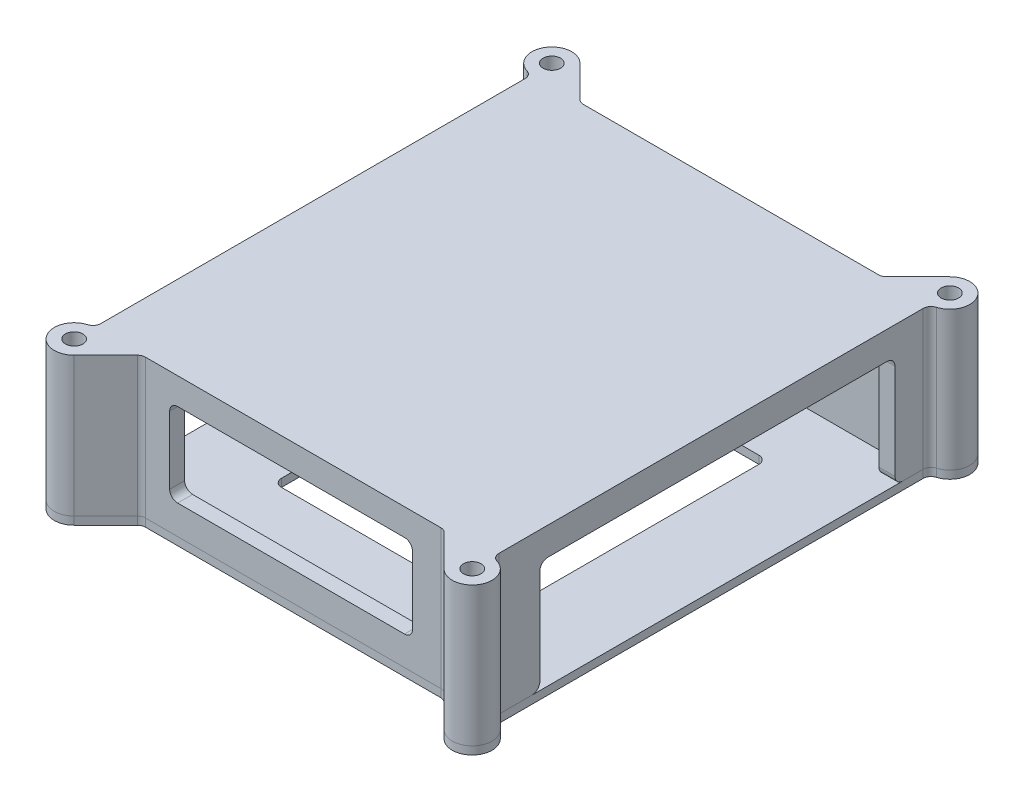
SolidWorks part; units mm, degrees
ref_plane "Front Plane" through (0, 0, 0) normal (0, 0, 1) x (1, 0, 0)
ref_plane "Top Plane" through (0, 0, 0) normal (0, 1, 0) x (1, 0, 0)
ref_plane "Right Plane" through (0, 0, 0) normal (1, 0, 0) x (0, 0, -1)
sketch "Sketch1" plane through (0, 0, 0) normal (0, 1, 0) x (1, 0, 0)
  line L1 (0, 0) -> (127, 0)
  line L2 (0, 0) -> (0, 139.7)
  line L3 (0, 139.7) -> (127, 139.7)
  line L4 (127, 0) -> (127, 139.7)
  dimension "D1" = 127
  dimension "D2" = 139.7
extrude "Boss-Extrude1" add sketch "Sketch1" along normal blind 44.45
sketch "Sketch3" plane through (0, 0, 0) normal (0, -1, 0) x (1, 0, 0)
  line L0 (0, -139.7) -> (0, 0) construction
  line L1 (6.35, -4.7625) -> (121.92, -4.7625)
  line L2 (6.35, -4.7625) -> (6.35, -135.8265)
  line L3 (6.35, -135.8265) -> (121.92, -135.8265)
  line L4 (121.92, -4.7625) -> (121.92, -135.8265)
  line L5 (0, 0) -> (127, 0) construction
  dimension "D1" = 115.57
  dimension "D2" = 131.064
  dimension "D3" = 6.35
  dimension "D4" = 4.7625
extrude "Cut-Extrude1" cut sketch "Sketch3" against normal blind 44
sketch "Sketch4" plane through (0, 0, -139.7) normal (0, 0, -1) x (-1, 0, 0)
  line L0 (-127, 0) -> (0, 0) construction
  line L1 (-101.6, 35.941) -> (-24.13, 35.941)
  line L2 (-101.6, 35.941) -> (-101.6, 9.271)
  line L3 (-101.6, 9.271) -> (-24.13, 9.271)
  line L4 (-24.13, 35.941) -> (-24.13, 9.271)
  line L7 (-127, 44.45) -> (-127, 0) construction
  dimension "D1" = 26.67
  dimension "D2" = 77.47
  dimension "D3" = 9.271
  dimension "D4" = 25.4
extrude "Cut-Extrude2" cut sketch "Sketch4" against normal blind 190.754
sketch "Sketch5" plane through (127, 0, 0) normal (1, 0, 0) x (0, 0, -1)
  line L0 (0, 44.45) -> (139.7, 44.45) construction
  line L1 (15.24, 35.56) -> (128.524, 35.56)
  line L2 (15.24, 35.56) -> (15.24, -11.43)
  line L3 (15.24, -11.43) -> (128.524, -11.43)
  line L4 (128.524, 35.56) -> (128.524, -11.43)
  line L6 (0, 44.45) -> (0, 0) construction
  dimension "D1" = 46.99
  dimension "D2" = 113.284
  dimension "D3" = 8.89
  dimension "D4" = 15.24
extrude "Cut-Extrude3" cut sketch "Sketch5" against normal blind 190.754 contours L2 L1 L4 L3
sketch "Sketch6" plane through (0, 0, 0) normal (0, -1, 0) x (-1, 0, 0)
  line L6 (0, 0) -> (-127, 0) construction
  line L7 (-127, 146.05) -> (0, 146.05) construction
  line L8 (-127, 146.05) -> (-127, -6.35) construction
  line L9 (-127, -6.35) -> (0, -6.35) construction
  line L10 (0, 146.05) -> (0, -6.35) construction
  line L12 (-122.5099, 150.5401) -> (-111.6697, 139.7)
  line L13 (-127, 139.7) -> (0, 139.7) construction
  line L14 (-4.4901, 150.5401) -> (-15.3303, 139.7)
  line L15 (-4.4901, -10.8401) -> (-15.3303, 0)
  line L16 (-122.5099, -10.8401) -> (-111.6697, 0)
  line L17 (-127, 0) -> (-111.6697, 0)
  line L18 (-15.3303, 0) -> (0, 0)
  line L19 (-127, 0) -> (-127, 15.24) construction
  line L20 (-127, 139.7) -> (0, 139.7)
  circle A0 centre (0, -6.35) radius 2.794
  circle A1 centre (-127, -6.35) radius 2.794
  circle A2 centre (0, 146.05) radius 2.794
  circle A3 centre (-127, 146.05) radius 2.794
  circle A4 centre (-127, -6.35) radius 6.35
  circle A5 centre (0, -6.35) radius 6.35
  circle A6 centre (0, 146.05) radius 6.35
  circle A7 centre (-127, 146.05) radius 6.35
  line M3 (-127, 0) -> (0, 0)
  dimension "D1" = 5.588
  dimension "D2" = 5.588
  dimension "D3" = 5.588
  dimension "D4" = 5.588
  dimension "D6" = 152.4
  dimension "D5" = 127
ref_plane "Plane1" through (63.5, 0, 0) normal (1, 0, 0) x (0, 0, -1)
ref_plane "Plane4" through (0, 0, -69.85) normal (0, 0, -1) x (-1, 0, 0)
extrude "Boss-Extrude2" add sketch "Sketch6" against normal through all contours A7 A3 | A7 L20 L12 | A6 L14 L20 | A4 A1 | A4 L16 M3 | A5 L15 M3 | A5 A0 | A6 A2
fillet "Fillet1" radius 2.54 24 edges at (0, 22.225, -139.7) (15.3303, 22.225, -139.7) (127, 22.225, -139.7) (127, 22.225, 0) (111.6697, 22.225, 0) (15.3303, 22.225, 0) (0, 22.225, 0) (111.6697, 22.225, -139.7) (24.13, 9.271, -2.3813) (101.6, 9.271, -2.3813) (101.6, 35.941, -2.3813) (24.13, 35.941, -2.3813) (24.13, 9.271, -137.7632) (101.6, 9.271, -137.7632) (101.6, 35.941, -137.7632) (24.13, 35.941, -137.7632) (3.175, 0, -128.524) (3.175, 35.56, -128.524) (3.175, 35.56, -15.24) (3.175, 0, -15.24) (124.46, 0, -15.24) (124.46, 35.56, -15.24) (124.46, 35.56, -128.524) (124.46, 0, -128.524)
sketch "Sketch7" plane through (0, 0, 0) normal (0, -1, 0) x (1, 0, 0)
  line L1 (127, -12.7) -> (127, -2.1694) construction
  line L2 (122.5099, 10.8401) -> (112.4137, 0.7439) construction
  line L3 (110.6176, 0) -> (16.3824, 0) construction
  line L4 (14.5863, 0.7439) -> (4.4901, 10.8401) construction
  line L5 (0, -2.1694) -> (0, -12.7) construction
  line L10 (127, -137.5306) -> (127, -131.064) construction
  line L16 (0, -131.064) -> (0, -137.5306) construction
  line L17 (4.4901, -150.5401) -> (14.5863, -140.4439) construction
  line L18 (16.3824, -139.7) -> (110.6176, -139.7) construction
  line L19 (112.4137, -140.4439) -> (122.5099, -150.5401) construction
  line L21 (127, -12.7) -> (127, -2.1694)
  line L22 (122.5099, 10.8401) -> (112.4137, 0.7439)
  line L23 (110.6176, 0) -> (16.3824, 0)
  line L24 (14.5863, 0.7439) -> (4.4901, 10.8401)
  line L25 (0, -2.1694) -> (0, -12.7)
  line L30 (127, -137.5306) -> (127, -131.064)
  line L36 (0, -131.064) -> (0, -137.5306)
  line L37 (4.4901, -150.5401) -> (14.5863, -140.4439)
  line L38 (16.3824, -139.7) -> (110.6176, -139.7)
  line L39 (112.4137, -140.4439) -> (122.5099, -150.5401)
  line L40 (0, -131.064) -> (0, -12.7)
  line L41 (127, -12.7) -> (127, -131.064)
  line L43 (27.1096, -30.1617) -> (99.4355, -30.1617)
  line L44 (27.1096, -30.1617) -> (27.1096, -115.2243)
  line L45 (27.1096, -115.2243) -> (99.4355, -115.2243)
  line L46 (99.4355, -30.1617) -> (99.4355, -115.2243)
  circle A0 centre (127, -146.05) radius 2.794 construction
  circle A1 centre (0, -146.05) radius 2.794 construction
  circle A2 centre (127, 6.35) radius 2.794 construction
  circle A3 centre (0, 6.35) radius 2.794 construction
  circle A4 centre (127, -146.05) radius 2.794
  circle A5 centre (0, -146.05) radius 2.794
  circle A6 centre (127, 6.35) radius 2.794
  circle A7 centre (0, 6.35) radius 2.794
  arc A8 (128.8143, 0.2647) -> (127, -2.1694) centre (129.54, -2.1694) ccw construction
  arc A9 (128.8143, 0.2647) -> (122.5099, 10.8401) centre (127, 6.35) ccw construction
  arc A10 (110.6176, 0) -> (112.4137, 0.7439) centre (110.6176, 2.54) ccw construction
  arc A11 (14.5863, 0.7439) -> (16.3824, 0) centre (16.3824, 2.54) ccw construction
  arc A12 (4.4901, 10.8401) -> (-1.8143, 0.2647) centre (0, 6.35) ccw construction
  arc A13 (0, -2.1694) -> (-1.8143, 0.2647) centre (-2.54, -2.1694) ccw construction
  arc A14 (-1.8143, -139.9647) -> (0, -137.5306) centre (-2.54, -137.5306) ccw construction
  arc A15 (-1.8143, -139.9647) -> (4.4901, -150.5401) centre (0, -146.05) ccw construction
  arc A16 (16.3824, -139.7) -> (14.5863, -140.4439) centre (16.3824, -142.24) ccw construction
  arc A17 (112.4137, -140.4439) -> (110.6176, -139.7) centre (110.6176, -142.24) ccw construction
  arc A18 (122.5099, -150.5401) -> (128.8143, -139.9647) centre (127, -146.05) ccw construction
  arc A19 (127, -137.5306) -> (128.8143, -139.9647) centre (129.54, -137.5306) ccw construction
  arc A20 (128.8143, 0.2647) -> (127, -2.1694) centre (129.54, -2.1694) ccw
  arc A21 (128.8143, 0.2647) -> (122.5099, 10.8401) centre (127, 6.35) ccw
  arc A22 (110.6176, 0) -> (112.4137, 0.7439) centre (110.6176, 2.54) ccw
  arc A23 (14.5863, 0.7439) -> (16.3824, 0) centre (16.3824, 2.54) ccw
  arc A24 (4.4901, 10.8401) -> (-1.8143, 0.2647) centre (0, 6.35) ccw
  arc A25 (0, -2.1694) -> (-1.8143, 0.2647) centre (-2.54, -2.1694) ccw
  arc A26 (-1.8143, -139.9647) -> (0, -137.5306) centre (-2.54, -137.5306) ccw
  arc A27 (-1.8143, -139.9647) -> (4.4901, -150.5401) centre (0, -146.05) ccw
  arc A28 (16.3824, -139.7) -> (14.5863, -140.4439) centre (16.3824, -142.24) ccw
  arc A29 (112.4137, -140.4439) -> (110.6176, -139.7) centre (110.6176, -142.24) ccw
  arc A30 (122.5099, -150.5401) -> (128.8143, -139.9647) centre (127, -146.05) ccw
  arc A31 (127, -137.5306) -> (128.8143, -139.9647) centre (129.54, -137.5306) ccw
  point P22 (25.745, -115.2243)
  point P26 (104.8941, -27.205)
  point P27 (27.1096, -30.1617)
extrude "Boss-Extrude3" add sketch "Sketch7" along normal blind 2.54 separate body
fillet "Fillet2" radius 2.54 4 edges at (99.4355, -1.27, -115.2243) (99.4355, -1.27, -30.1617) (27.1096, -1.27, -115.2243) (27.1096, -1.27, -30.1617)
